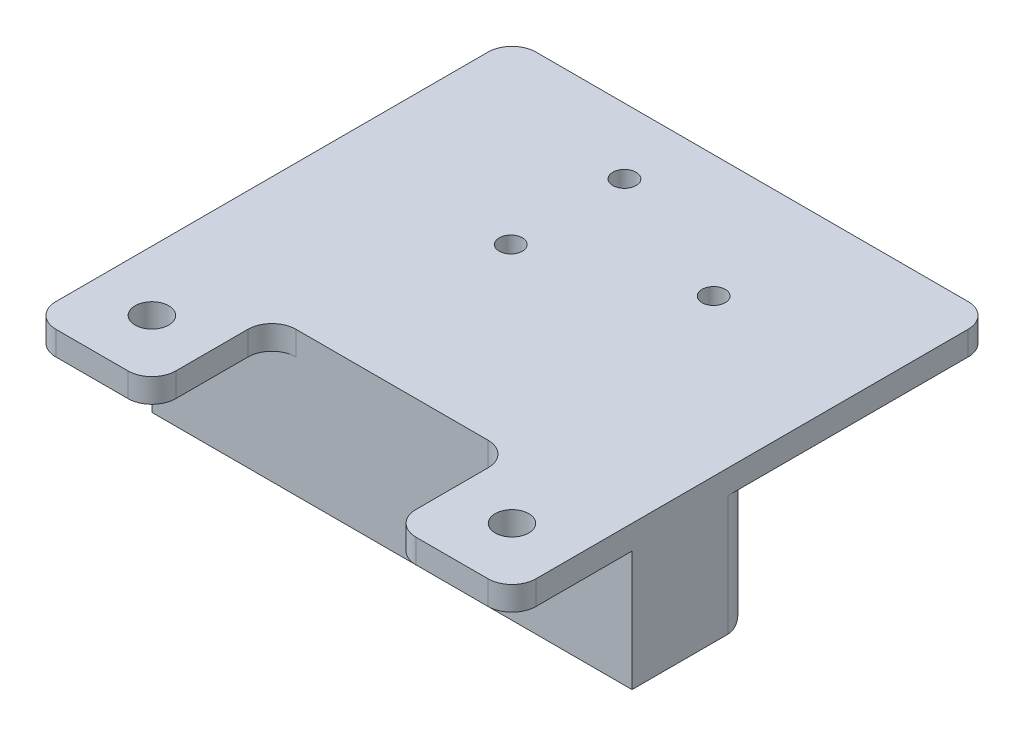
SolidWorks part; units mm, degrees
material "ABS"
ref_plane "前视基准面" through (0, 0, 0) normal (0, 0, 1) x (1, 0, 0)
ref_plane "上视基准面" through (0, 0, 0) normal (0, 1, 0) x (1, 0, 0)
ref_plane "右视基准面" through (0, 0, 0) normal (1, 0, 0) x (0, 0, -1)
other "Configuration Table"
sketch "草图1" plane through (0, 0, 0) normal (0, 1, 0) x (1, 0, 0)
  line L0 (0, 99.2951) -> (0, -89.4557) construction
  line L1 (-30, -7.5) -> (30, -7.5) construction
  line L2 (-30, -7.5) -> (-30, 7.5) construction
  line L3 (-30, 7.5) -> (30, 7.5) construction
  line L4 (30, -7.5) -> (30, 7.5) construction
  line L5 (-30, -7.5) -> (30, 7.5) construction
  line L6 (-30, 7.5) -> (30, -7.5) construction
  line L7 (-15, 7.5) -> (-15, -7.5)
  line L8 (-30, 7.5) -> (30, 7.5) construction
  line L9 (-30, 7.5) -> (-30, 52.5) construction
  line L10 (-30, 52.5) -> (30, 52.5) construction
  line L11 (30, 7.5) -> (30, 52.5) construction
  line L12 (-15, -7.5) -> (-30, -7.5)
  line L13 (-30, -7.5) -> (-30, 52.5)
  line L14 (-30, 52.5) -> (30, 52.5)
  line L15 (30, 52.5) -> (30, -7.5)
  line L16 (30, -7.5) -> (15, -7.5)
  line L17 (15, -7.5) -> (15, 7.5)
  line L18 (15, 7.5) -> (-15, 7.5)
  line L19 (36.4828, 0) -> (-40.2755, 0) construction
  line L20 (-7.75, 37.2) -> (10.5, 37.2) construction
  line L21 (-7.75, 44.3) -> (-7.75, 30.1) construction
  circle A0 centre (-22.5, 0) radius 2.1
  circle A1 centre (22.5, 0) radius 2.1
  circle A2 centre (-7.75, 44.3) radius 1.45
  circle A3 centre (10.5, 37.2) radius 1.45
  circle A4 centre (-7.75, 30.1) radius 1.45
  point P0 (0, 0)
  point P25 (-7.75, 37.2)
  dimension "D5" = 4.2
  dimension "D6" = 7.5
  dimension "D9" = 2.9
  dimension "D1" = 60
  dimension "D2" = 60
  dimension "D3" = 15
  dimension "D4" = 15
  dimension "D7" = 14.2
  dimension "D8" = 18.25
  dimension "D10" = 29.7
  dimension "D11" = 10.5
extrude "凸台-拉伸1" add sketch "草图1" along normal blind 3
sketch "草图2" plane through (0, 0, 0) normal (0, -1, 0) x (1, 0, 0)
  line L0 (-30, -52.5) -> (-30, 7.5) construction
  line L1 (-30, -7.5) -> (30, -7.5)
  line L2 (-30, -7.5) -> (-30, -22.5)
  line L3 (-30, -22.5) -> (30, -22.5)
  line L4 (30, -7.5) -> (30, -22.5)
  line L5 (30, 7.5) -> (30, -52.5) construction
  line L6 (-15, -7.5) -> (15, -7.5) construction
  dimension "D1" = 15
extrude "凸台-拉伸2" add sketch "草图2" along normal blind 15
fillet "圆角1" radius 3 11 edges at (30, -7.5, -22.5) (-30, -7.5, -22.5) (0, -15, -22.5) (-30, 1.5, -52.5) (30, 1.5, -52.5) (30, 1.5, 7.5) (15, 1.5, 7.5) (-15, 1.5, 7.5) (-30, 1.5, 7.5) (15, 1.5, -7.5) (-15, 1.5, -7.5)
